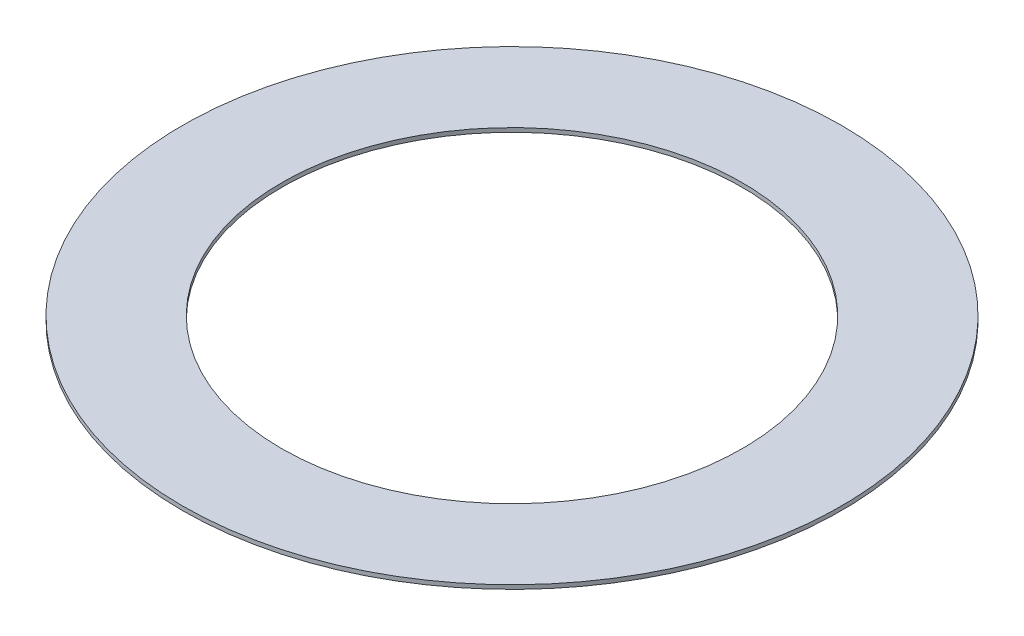
SolidWorks part; units mm, degrees
ref_plane "Front Plane" through (0, 0, 0) normal (0, 0, 1) x (1, 0, 0)
ref_plane "Top Plane" through (0, 0, 0) normal (0, 1, 0) x (1, 0, 0)
ref_plane "Right Plane" through (0, 0, 0) normal (1, 0, 0) x (0, 0, -1)
sketch "Sketch1" plane through (0, 0, 0) normal (0, 1, 0) x (1, 0, 0)
  circle A0 centre (0, 0) radius 243.0724
  circle A1 centre (0, 0) radius 169.8912
extrude "Boss-Extrude1" add sketch "Sketch1" along normal blind 3
